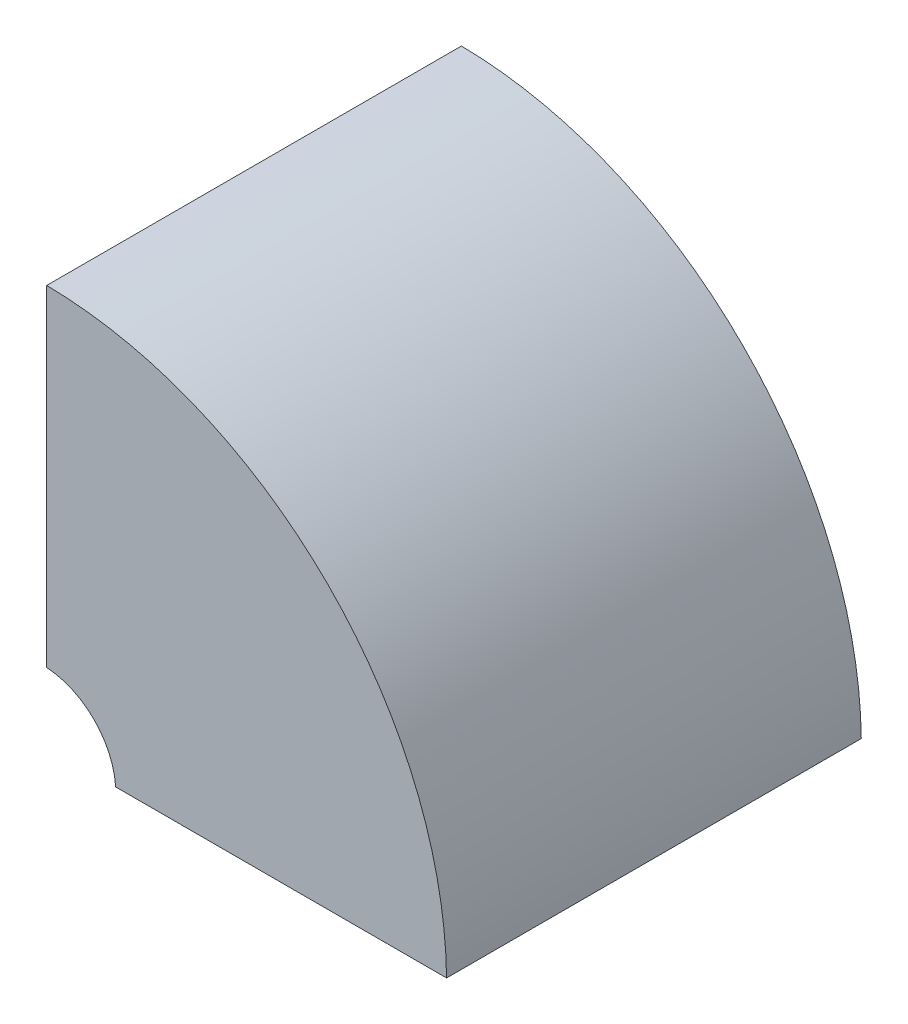
SolidWorks part; units mm, degrees
ref_plane "Front Plane" through (0, 0, 0) normal (0, 0, 1) x (1, 0, 0)
ref_plane "Top Plane" through (0, 0, 0) normal (0, 1, 0) x (1, 0, 0)
ref_plane "Right Plane" through (0, 0, 0) normal (1, 0, 0) x (0, 0, -1)
sketch "Sketch1" plane through (0, 0, 0) normal (0, 0, 1) x (1, 0, 0)
  line L0 (0.5, 40.997) -> (0.5, 7.4833)
  line L1 (7.4833, 0.5) -> (40.997, 0.5)
  arc A0 (7.4833, 0.5) -> (0.5, 7.4833) centre (0, 0) ccw
  arc A1 (40.997, 0.5) -> (0.5, 40.997) centre (0, 0) ccw
  dimension "D1" = 41
extrude "Boss-Extrude1" add sketch "Sketch1" against normal blind 42
